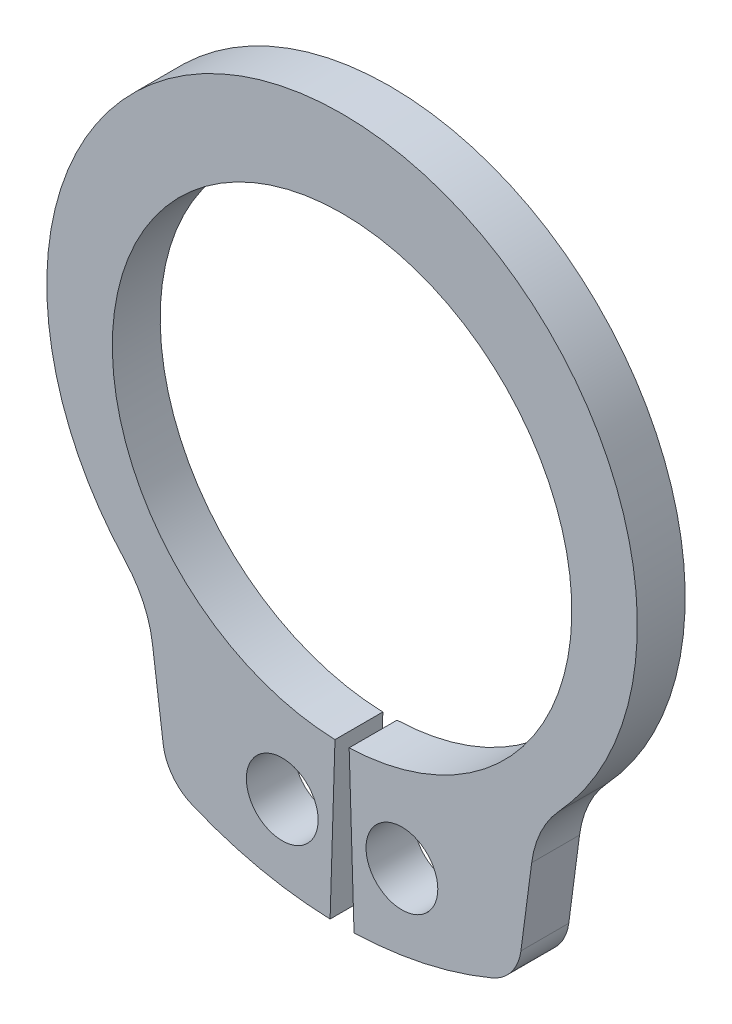
SolidWorks part; units mm, degrees
ref_plane "Plane1" through (0, 0, 0) normal (0, 0, 1) x (1, 0, 0)
ref_plane "Plane2" through (0, 0, 0) normal (0, 1, 0) x (1, 0, 0)
ref_plane "Plane3" through (0, 0, 0) normal (1, 0, 0) x (0, 0, -1)
sketch "Clipboard" plane through (0, 0, 0) normal (0, 0, 1) x (1, 0, 0)
  line L0 (0, 0) -> (1.8, 0)
  line L1 (0, 0) -> (0, 1.08)
  line L2 (0, 0) -> (0, -3.3)
  circle A0 centre (0, 0) radius 0.75
  circle A1 centre (0, 0) radius 5
  dimension "HoleDia" = 1.5
  dimension "ShaftDia" = 10
  dimension "LargeSection" = 1.8
  dimension "SmallSection" = 1.08
  dimension "LugSection" = 3.3
sketch "BodySke" plane through (0, 0, 0) normal (0, 0, 1) x (1, 0, 0)
  line L0 (-1.5431, 0) -> (1.5431, 0) construction
  line L1 (0, 0) -> (0, 6.6) construction
  line L2 (0.1481, -4.7977) -> (0.25, -8.0961)
  line L3 (-0.1481, -4.7977) -> (-0.25, -8.0961)
  line L4 (0, 0) -> (6.16, -5.2597) construction
  line L5 (0, 0) -> (-6.16, -5.2597) construction
  line L7 (3.9613, -4.9702) -> (3.7364, -6.6784)
  line L8 (-3.9613, -4.9702) -> (-3.7364, -6.6784)
  circle A0 centre (0, 0) radius 4.8 construction
  arc A1 (0.1481, -4.7977) -> (-0.1481, -4.7977) centre (0, 0) ccw
  arc A2 (4.4717, -3.8181) -> (-4.4717, -3.8181) centre (0, 0.4312) ccw construction
  arc A3 (0.25, -8.0961) -> (3.1316, -7.4702) centre (0, 0) ccw
  arc A4 (4.5311, -3.7548) -> (3.9613, -4.9702) centre (6.16, -5.2597) ccw
  arc A5 (-3.9613, -4.9702) -> (-4.5311, -3.7548) centre (-6.16, -5.2597) ccw
  arc A6 (-3.1316, -7.4702) -> (-0.25, -8.0961) centre (0, 0) ccw
  arc A7 (4.5311, -3.7548) -> (-4.5311, -3.7548) centre (0, 0.4312) ccw
  arc A8 (-3.9253, -5.2435) -> (3.9253, -5.2435) centre (0, 0) ccw construction
  circle A9 centre (1.25, -6.4296) radius 0.75
  circle A10 centre (-1.25, -6.4296) radius 0.75
  arc A11 (3.7364, -6.6784) -> (3.1316, -7.4702) centre (2.745, -6.5479) cw
  arc A12 (-3.7364, -6.6784) -> (-3.1316, -7.4702) centre (-2.745, -6.5479) ccw
  point P28 (3.6646, -7.2236)
  point P31 (-3.6646, -7.2236)
  dimension "GrooveDia" = 9.6
  dimension "D3" = 1
  dimension "LugRad" = 8.1
  dimension "HoleOffsetRad" = 6.55
  dimension "HoleDia" = 1.5
  dimension "D2" = 15
  dimension "LargeRad" = 6.6
  dimension "SmallRad" = 5.88
  dimension "Gap" = 0.5
  dimension "SmallAngle" = 99.016
  dimension "HoleSpacing" = 2.5
extrude "Body" add sketch "BodySke" against normal blind 1
sketch "NotSke" plane through (0, 0, 0) normal (0, 0, 1) x (1, 0, 0)
  line L0 (1.25, -5.6796) -> (1.25, -7.1796)
  line L1 (1.25, -7.1796) -> (-1.25, -7.1796)
  line L2 (-1.25, -7.1796) -> (-1.25, -5.6796)
  line L3 (-1.25, -5.6796) -> (1.25, -5.6796)
  circle A0 centre (1.25, -6.4296) radius 0.75 construction
  circle A1 centre (-1.25, -6.4296) radius 0.75 construction
extrude "Notch" [suppressed] cut sketch "NotSke" against normal through all
sketch "UnlSke" plane through (0, 0, 0) normal (0, 0, 1) x (1, 0, 0)
  line L0 (3.1316, -3.6377) -> (3.1316, -7.4702)
  line L1 (-3.1316, -3.6377) -> (-3.1316, -7.4702)
  arc A0 (3.1316, -3.6377) -> (-3.1316, -3.6377) centre (0, 0) ccw
  arc A1 (3.1316, -7.4702) -> (-3.1316, -7.4702) centre (0, 0) ccw
  arc A4 (-3.1316, -7.4702) -> (-0.25, -8.0961) centre (0, 0) ccw construction
  arc A5 (0.1481, -4.7977) -> (-0.1481, -4.7977) centre (0, 0) ccw construction
extrude "Unlug" [suppressed] add sketch "UnlSke" against normal through all
equation "' \"ShaftDia@Clipboard\" = 3"
equation "' \"Thickness@Body\" = 0.4"
equation "' \"GrooveDia@BodySke\" = 2.8"
equation "' \"LugSection@Clipboard\" = 1.9"
equation "' \"LargeSection@Clipboard\" = 0.8"
equation "' \"HoleDia@Clipboard\" = 0.8"
equation "' \"ShaftDia@Clipboard\" = 9"
equation "' \"Thickness@Body\" = 1"
equation "' \"GrooveDia@BodySke\" = 8.6"
equation "' \"LugSection@Clipboard\" = 3.3"
equation "' \"LargeSection@Clipboard\" = 1.7"
equation "' \"HoleDia@Clipboard\" = 1.2"
equation "\"SmallSection@Clipboard\" =  \"LargeSection@Clipboard\" * 0.6"
equation "\"Gap@BodySke\" =  \"Thickness@Body\" / 2"
equation "\"LargeRad@BodySke\" =  \"GrooveDia@BodySke\" / 2 +  \"LargeSection@Clipboard\""
equation "\"SmallRad@BodySke\" =  \"GrooveDia@BodySke\" / 2 +  \"SmallSection@Clipboard\""
equation "\"LugRad@BodySke\" = \"GrooveDia@BodySke\" / 2 + \"LugSection@Clipboard\""
equation "\"HoleOffsetRad@BodySke\" = (  \"ShaftDia@Clipboard\" / 2 + \"LugRad@BodySke\" ) / 2"
equation "\"HoleSpacing@BodySke\" = \"Gap@BodySke\"  * 2 +  \"HoleDia@Clipboard\""
equation "\"HoleDia@BodySke\" =  \"HoleDia@Clipboard\""
equation "\"SmallAngle@BodySke\" = atn(\"HoleSpacing@BodySke\" / 2 / sqr(\"HoleOffsetRad@BodySke\"  * \"HoleOffsetRad@BodySke\" - (\"HoleSpacing@BodySke\" / 2) * (\"HoleSpacing@BodySke\" / 2) ))  * 9 * ( 180 / 3.141593)"
